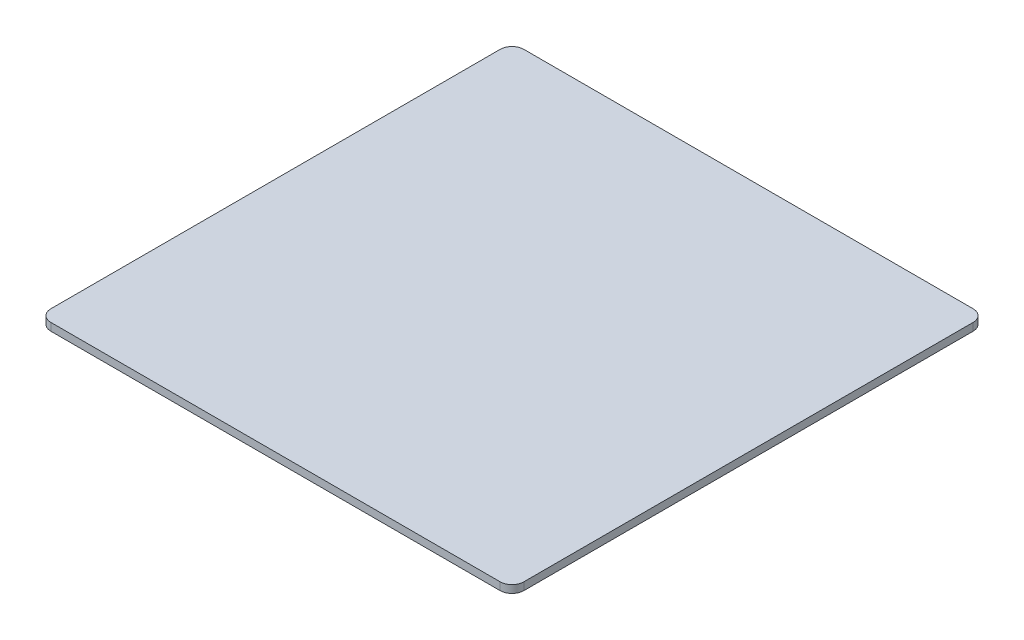
SolidWorks part; units mm, degrees
ref_plane "Front Plane" through (0, 0, 0) normal (0, 0, 1) x (1, 0, 0)
ref_plane "Top Plane" through (0, 0, 0) normal (0, 1, 0) x (1, 0, 0)
ref_plane "Right Plane" through (0, 0, 0) normal (1, 0, 0) x (0, 0, -1)
sketch "Sketch3" plane through (0, 0, 0) normal (0, 1, 0) x (1, 0, 0)
  line L1 (0, 0) -> (-203.2, 0)
  line L2 (0, 0) -> (0, 203.2)
  line L3 (0, 203.2) -> (-203.2, 203.2)
  line L4 (-203.2, 0) -> (-203.2, 203.2)
  dimension "D1" = 203.2
  dimension "D2" = 203.2
extrude "Boss-Extrude1" add sketch "Sketch3" along normal blind 3.302
fillet "Fillet1" radius 5.08 1 edges at (-203.2, 1.651, 0)
fillet "Fillet2" radius 5.08 1 edges at (0, 1.651, 0)
fillet "Fillet3" radius 5.08 1 edges at (0, 1.651, -203.2)
fillet "Fillet4" radius 5.08 1 edges at (-203.2, 1.651, -203.2)
